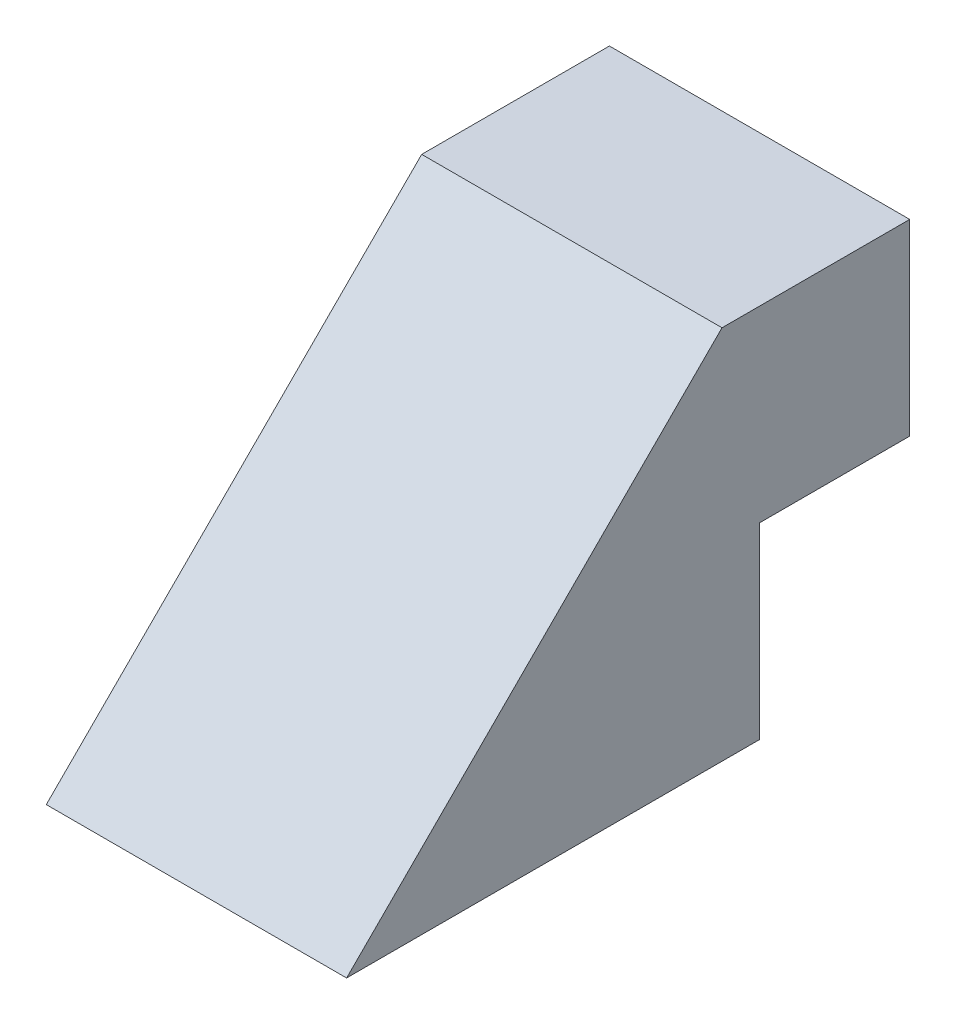
SolidWorks part; units mm, degrees
ref_plane "Front Plane" through (0, 0, 0) normal (0, 0, 1) x (1, 0, 0)
ref_plane "Top Plane" through (0, 0, 0) normal (0, 1, 0) x (1, 0, 0)
ref_plane "Right Plane" through (0, 0, 0) normal (1, 0, 0) x (0, 0, -1)
sketch "Sketch1" plane through (0, 0, 0) normal (0, 1, 0) x (1, 0, 0)
  line L1 (0, 0) -> (4, 0)
  line L2 (0, 0) -> (0, 0.5)
  line L3 (0, 0.5) -> (4, 0.5)
  line L4 (4, 0) -> (4, 0.5)
  dimension "D1" = 0.5
  dimension "D2" = 4
extrude "Boss-Extrude1" add sketch "Sketch1" along normal blind 5
sketch "Sketch2" plane through (0, 0, -0.5) normal (0, 0, -1) x (-1, 0, 0)
  line L0 (0, 5) -> (0, 0) construction
  line L1 (-4, 5) -> (0, 5)
  line L2 (-4, 5) -> (-4, 2.5)
  line L3 (-4, 2.5) -> (0, 2.5)
  line L4 (0, 5) -> (0, 2.5)
extrude "Boss-Extrude2" add sketch "Sketch2" along normal blind 2
sketch "Sketch4" plane through (0, 0, 0) normal (-1, 0, 0) x (0, 0, 1)
  line L5 (0, 5) -> (0, 0)
  line L6 (0, 0) -> (5, 0)
  line L7 (5, 0) -> (0, 5)
  dimension "D1" = 5
extrude "Boss-Extrude4" add sketch "Sketch4" against normal blind 4
